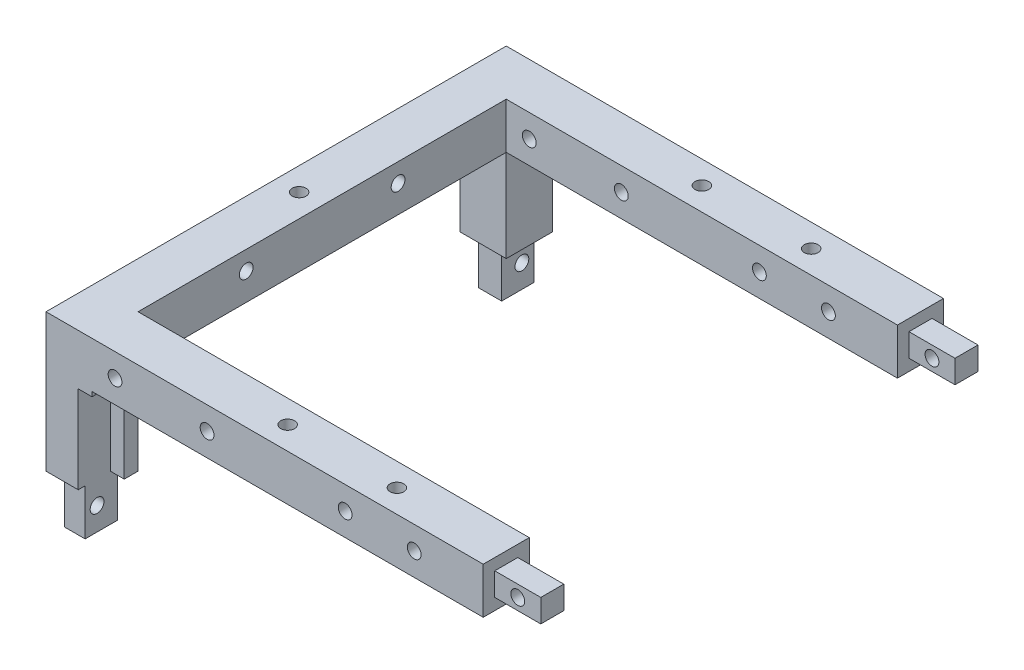
SolidWorks part; units mm, degrees
ref_plane "Front Plane" through (0, 0, 0) normal (0, 0, 1) x (1, 0, 0)
ref_plane "Top Plane" through (0, 0, 0) normal (0, 1, 0) x (1, 0, 0)
ref_plane "Right Plane" through (0, 0, 0) normal (1, 0, 0) x (0, 0, -1)
sketch "Sketch1" plane through (0, 0, 0) normal (0, 1, 0) x (1, 0, 0)
  line L0 (0, 0) -> (0, 200)
  line L1 (0, 200) -> (320, 200)
  line L2 (320, 200) -> (320, 0)
  line L3 (320, 0) -> (0, 0)
  line L4 (300, 20) -> (20, 20)
  line L5 (20, 20) -> (20, 180)
  line L6 (20, 180) -> (300, 180)
  line L7 (300, 180) -> (300, 20)
  dimension "D1" = 280
  dimension "D2" = 320
  dimension "D3" = 200
  dimension "D4" = 160
  dimension "D5" = 20
  dimension "D6" = 20
extrude "Boss-Extrude1" add sketch "Sketch1" along normal blind 20
sketch "Sketch2" plane through (0, 20, 0) normal (0, 1, 0) x (1, 0, 0)
  line L5 (0, 0) -> (320, 0) construction
  line L6 (320, 200) -> (190, 200)
  line L7 (320, 200) -> (320, 0)
  line L8 (320, 0) -> (190, 0)
  line L9 (190, 200) -> (190, 0)
  dimension "D1" = 130
extrude "Cut-Extrude1" cut sketch "Sketch2" against normal blind 20
sketch "Sketch5" plane through (0, 0, 0) normal (0, -1, 0) x (1, 0, 0)
  line L0 (0, -100) -> (110.8242, -100) construction
  line L1 (0, -200) -> (0, 0) construction
  line L3 (0, 0) -> (20, 0)
  line L4 (0, 0) -> (0, -20)
  line L5 (0, -20) -> (20, -20)
  line L6 (20, 0) -> (20, -20)
  line L14 (0, -180) -> (20, -180)
  line L15 (20, -200) -> (20, -180)
  line L16 (0, -200) -> (20, -200)
  line L17 (0, -200) -> (0, -180)
extrude "Boss-Extrude4" add sketch "Sketch5" along normal blind 40
sketch "Sketch8" plane through (0, -40, 0) normal (0, -1, 0) x (1, 0, 0)
  line L0 (0, -20) -> (20, -20) construction
  line L1 (15, -3) -> (5, -3)
  line L2 (15, -3) -> (15, -17)
  line L3 (15, -17) -> (5, -17)
  line L4 (5, -3) -> (5, -17)
  line L5 (20, -20) -> (20, 0) construction
  dimension "D1" = 14
  dimension "D2" = 10
  dimension "D3" = 3
  dimension "D4" = 5
extrude "Boss-Extrude5" add sketch "Sketch8" along normal blind 20
sketch "Sketch9" plane through (0, -40, 0) normal (0, -1, 0) x (1, 0, 0)
  line L0 (20, -200) -> (20, -180) construction
  line L1 (15, -183) -> (5, -183)
  line L2 (15, -183) -> (15, -197)
  line L3 (15, -197) -> (5, -197)
  line L4 (5, -183) -> (5, -197)
  line L5 (0, -200) -> (20, -200) construction
  dimension "D1" = 14
  dimension "D2" = 10
  dimension "D3" = 5
  dimension "D4" = 3
extrude "Boss-Extrude6" add sketch "Sketch9" along normal blind 20
sketch "Sketch10" plane through (190, 0, 0) normal (1, 0, 0) x (0, 0, -1)
  line L0 (180, 20) -> (180, 0) construction
  line L1 (195, 15) -> (185, 15)
  line L2 (195, 15) -> (195, 5)
  line L3 (195, 5) -> (185, 5)
  line L4 (185, 15) -> (185, 5)
  line L5 (200, 0) -> (180, 0) construction
  line L6 (180, 20) -> (20, 20) construction
  line L7 (20, 20) -> (100, 20) construction
  line L8 (100, 20) -> (100, -48.6073) construction
  line L9 (5, 5) -> (15, 5)
  line L10 (15, 15) -> (15, 5)
  line L11 (5, 15) -> (15, 15)
  line L12 (5, 15) -> (5, 5)
  dimension "D1" = 10
  dimension "D2" = 10
  dimension "D3" = 5
  dimension "D4" = 5
extrude "Boss-Extrude7" add sketch "Sketch10" along normal blind 20
sketch "Sketch11" plane through (0, 20, 0) normal (0, 1, 0) x (1, 0, 0)
  line L0 (0, 100) -> (227.0659, 100) construction
  line L1 (0, 200) -> (0, 0) construction
  line L2 (190, 200) -> (190, 180) construction
  line L3 (190, 200) -> (0, 200) construction
  circle A0 centre (142.5, 190) radius 3
  circle A1 centre (95, 190) radius 3
  circle A2 centre (10, 100) radius 3
  circle A3 centre (142.5, 10) radius 3
  circle A4 centre (95, 10) radius 3
  dimension "D1" = 6
  dimension "D2" = 6
  dimension "D3" = 6
  dimension "D7" = 10
  dimension "D8" = 10
  dimension "D4" = 47.5
  dimension "D5" = 95
  dimension "D6" = 10
  dimension "D9" = 95
  dimension "D10" = 142.5
extrude "Cut-Extrude2" cut sketch "Sketch11" against normal blind 30
sketch "Sketch13" plane through (0, 0, 0) normal (-1, 0, 0) x (0, 0, 1)
  line L0 (-100, 20) -> (-100, -73.9116) construction
  line L1 (-200, 20) -> (0, 20) construction
  line L2 (-180, 20) -> (-20, 20) construction
  line L3 (-3, -60) -> (-17, -60) construction
  line L4 (-3, -60) -> (-3, -40) construction
  circle A1 centre (-8.2, -50) radius 3
  circle A2 centre (-67, 11.8) radius 3
  circle A3 centre (-133, 11.8) radius 3
  circle A4 centre (-191.8, -50) radius 3
  dimension "D1" = 6
  dimension "D2" = 6
  dimension "D5" = 8.2
  dimension "D6" = 8.2
  dimension "D7" = 6
  dimension "D9" = 5.2
  dimension "D3" = 33
  dimension "D4" = 33
  dimension "D8" = 10
extrude "Cut-Extrude3" cut sketch "Sketch13" against normal blind 30
sketch "Sketch14" plane through (0, 0, -200) normal (0, 0, -1) x (-1, 0, 0)
  line L0 (0, 20) -> (0, -40) construction
  line L1 (-190, 0) -> (-20, 0) construction
  circle A0 centre (-160, 10) radius 3
  circle A1 centre (-30, 10) radius 3
  circle A2 centre (-130, 10) radius 3
  circle A3 centre (-70, 10) radius 3
  dimension "D1" = 160
  dimension "D2" = 6
  dimension "D3" = 10
  dimension "D4" = 10
  dimension "D5" = 6
  dimension "D6" = 30
  dimension "D7" = 6
  dimension "D8" = 6
  dimension "D9" = 70
  dimension "D10" = 130
extrude "Cut-Extrude4" cut sketch "Sketch14" against normal through all both and the other way through all
sketch "Sketch16" plane through (0, 0, -5) normal (0, 0, 1) x (1, 0, 0)
  line L0 (210, 15) -> (210, 5) construction
  line L1 (210, 5) -> (190, 5) construction
  circle A0 centre (200, 10) radius 3
  dimension "D1" = 10
  dimension "D2" = 5
  dimension "D3" = 6
extrude "Cut-Extrude5" cut sketch "Sketch16" against normal through all both and the other way through all
sketch "Sketch17" plane through (20, 0, 0) normal (1, 0, 0) x (0, 0, -1)
  line L1 (0, -40) -> (14, -40)
  line L2 (0, -40) -> (0, -2)
  line L3 (0, -2) -> (14, -2)
  line L4 (14, -40) -> (14, -2)
  dimension "D1" = 14
  dimension "D2" = 38
extrude "Cut-Extrude6" cut sketch "Sketch17" against normal blind 5
sketch "Sketch18" plane through (15, 0, 0) normal (1, 0, 0) x (0, 0, -1)
  line L0 (0, -2) -> (14, -2)
  line L1 (14, -2) -> (14, -40)
  line L2 (14, -40) -> (17, -40)
  line L3 (17, -40) -> (17, -60)
  line L4 (17, -60) -> (3, -60)
  line L5 (3, -60) -> (3, -40)
  line L6 (3, -40) -> (0, -40)
  line L7 (0, -40) -> (0, -2)
extrude "Cut-Extrude7" cut sketch "Sketch18" against normal blind 1
